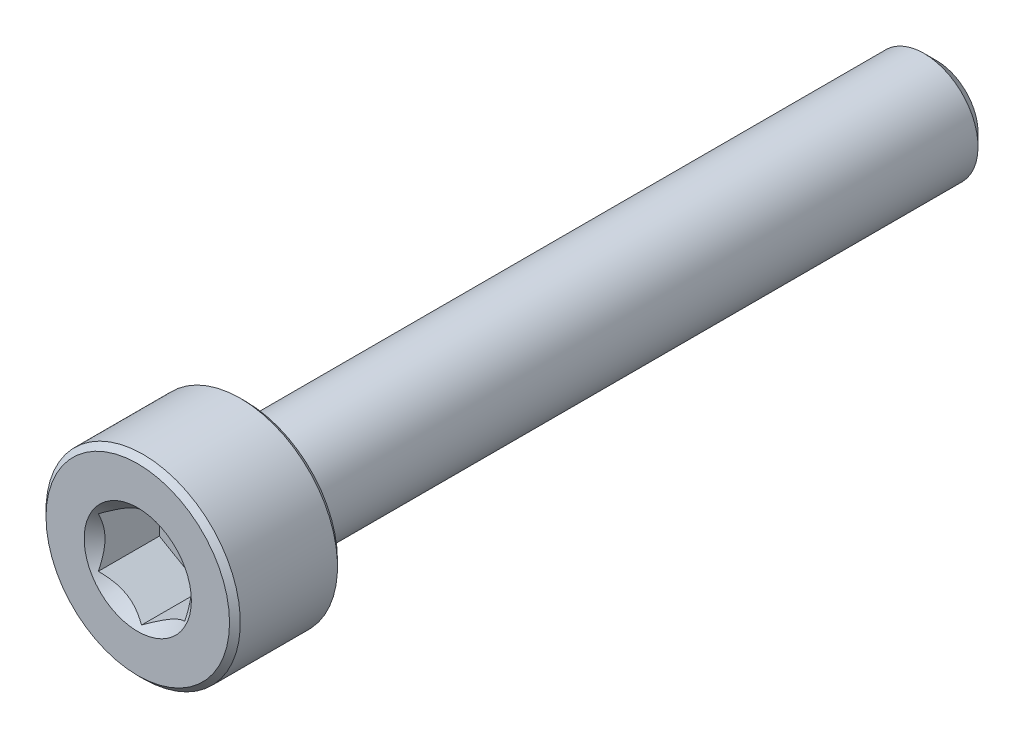
SolidWorks part; units mm, degrees
ref_plane "Front Plane" through (0, 0, 0) normal (0, 0, 1) x (1, 0, 0)
ref_plane "Top Plane" through (0, 0, 0) normal (0, 1, 0) x (1, 0, 0)
ref_plane "Right Plane" through (0, 0, 0) normal (1, 0, 0) x (0, 0, -1)
sketch "Sketch1" plane through (0, 0, 0) normal (1, 0, 0) x (0, 0, -1)
  line L0 (-9.25, 0) -> (9.25, 0) construction
  line L1 (9.25, 0) -> (9.25, 0.9577) construction
  line L2 (9.25, 0.9577) -> (8.9577, 1.25) construction
  line L3 (8.9577, 1.25) -> (8.9125, 1.25) construction
  line L4 (8.9125, 1.25) -> (-6.75, 1.25) construction
  line L5 (-6.75, 1.25) -> (-6.75, 2.25) construction
  line L6 (-6.75, 2.25) -> (-9.25, 2.25) construction
  line L7 (-9.25, 2.25) -> (-9.25, 0) construction
  line L8 (9.25, 0.9577) -> (9.25, 1.25) construction
  line L9 (9.2219, 1.2987) -> (9.4469, 0.909) construction
  line L10 (9.4469, 0.909) -> (9.6719, 1.2987) construction
  line L11 (9.6719, 1.2987) -> (9.2219, 1.2987) construction
  line L12 (9.4469, 1.2987) -> (9.4469, 1.25) construction
  line L13 (9.4469, 0.909) -> (9.4469, 0.9577) construction
  line L14 (9.4187, 0.9577) -> (9.475, 0.9577) construction
  line L15 (9.25, 1.25) -> (9.6437, 1.25) construction
  line L16 (9.2359, 1.2744) -> (9.6578, 1.2744) construction
  line L17 (9.25, 0) -> (9.25, -1.25) construction
  line L18 (-6.875, 2.25) -> (-6.75, 2.125) construction
  line L19 (-9.125, 2.25) -> (-9.25, 2.125) construction
  line L20 (-6.75, 1.25) -> (-6.75, 0) construction
  line L21 (-6.75, 0.625) -> (-1.4167, 0.625) construction
  line L22 (-1.4167, 0.625) -> (3.9167, 0.625) construction
  line L23 (3.9167, 0.625) -> (9.25, 0.625) construction
  line L24 (-1.4167, 0.625) -> (-1.4167, 1.25) construction
  line L25 (-1.4167, 1.25) -> (-1.4167, 2.25) construction
  line L26 (3.9167, 0.625) -> (3.9167, 2.25) construction
  point P0 (-9.25, 1)
  point P3 (8.125, 1.25)
  point P4 (0, 0)
  point P18 (3.9167, 1.25)
  point P22 (9.4469, 0.9577)
  point P24 (8.9125, 1.25)
  point P25 (9.4469, 1.25)
  point P28 (9.4469, 1.2744)
  point P29 (8.125, -1.25)
  point P30 (-1.4167, 1.25)
  point P31 (-8, 2.25)
  point P37 (-7.1875, 2.25)
  point P38 (-9.0625, 2.25)
  point P45 (-1.4167, 0.625)
  point P46 (3.9167, 0.625)
  dimension "D2" = 0.0563
  dimension "D7" = 0.125
  dimension "D8" = 0.125
  dimension "D9" = 0.125
  dimension "D10" = 0.0625
  dimension "D11" = 0.3125
  dimension "Drive Size" = 2
  dimension "Head Diameter" = 4.5
  dimension "Head Height" = 2.5
  dimension "Thread Pitch" = 0.45
  dimension "Thread Dia" = 2.5
  dimension "Length" = 16
  dimension "D12" = 0.3375
  dimension "D4" = 1.125
  dimension "D3" = 45
sketch "Sketch2" plane through (0, 0, 0) normal (1, 0, 0) x (0, 0, -1)
  line L0 (-9.25, 0) -> (-9.25, 2.125)
  line L1 (-9.125, 2.25) -> (-6.875, 2.25)
  line L2 (-6.75, 2.125) -> (-6.75, 1.375)
  line L4 (8.9577, 1.25) -> (9.25, 0.9577)
  line L5 (9.25, 0.9577) -> (9.25, 0)
  line L6 (-6.75, 2.25) -> (-9.25, 2.25) construction
  line L7 (9.25, 0) -> (-9.25, 0)
  line L8 (-9.125, 2.25) -> (-9.25, 2.125) construction
  line L10 (-9.125, 2.25) -> (-9.25, 2.125)
  line L14 (-6.875, 2.25) -> (-6.75, 2.125) construction
  line L16 (-6.875, 2.25) -> (-6.75, 2.125)
  line L17 (-6.75, 1.25) -> (-6.75, 2.25) construction
  line L19 (-6.625, 1.25) -> (8.9577, 1.25)
  line L20 (8.9125, 1.25) -> (-6.75, 1.25) construction
  arc A1 (-6.75, 1.375) -> (-6.625, 1.25) centre (-6.625, 1.375) ccw
  dimension "D3" = 0.125
revolve "Revolve1" add sketch "Sketch2" angle 360 about L7
sketch "Sketch3" plane through (0, 0, 9.25) normal (0, 0, 1) x (1, 0, 0)
  line L1 (1, -0.5774) -> (1, 0.5774)
  line L2 (1, 0.5774) -> (0, 1.1547)
  line L3 (0, 1.1547) -> (-1, 0.5774)
  line L4 (-1, 0.5774) -> (-1, -0.5774)
  line L5 (-1, -0.5774) -> (0, -1.1547)
  line L6 (0, -1.1547) -> (1, -0.5774)
  circle A0 centre (0, 0) radius 1 construction
  circle A1 centre (0, 0) radius 2.25 construction
  circle A2 centre (0, 0) radius 2.25 construction
  circle A3 centre (0, 0) radius 1.1547 construction
  point P13 (0, 0)
  dimension "D1" = 2.3094
extrude "Cut-Extrude1" cut sketch "Sketch3" against normal offset from surface (1.5 mm away) 1 up to face at (0, 2.125, 6.75)
sketch "Sketch4" plane through (0, 0, 9.25) normal (0, 0, 1) x (1, 0, 0)
  circle A0 centre (0, 0) radius 1.2413
  dimension "D1" = 2.4826
extrude "Cut-Extrude2" cut sketch "Sketch4" against normal up to vertex (1.25 mm away) draft 45 up to point (0, 2.25, 8)
sketch "Sketch11" plane through (0, 0, 0) normal (1, 0, 0) x (0, 0, -1)
  line L0 (-9.25, 0) -> (9.25, 0) construction
  line L1 (-9.25, 0) -> (9.25, 0) construction
  line L2 (-3.75, 0) -> (-3.75, 1.25) construction
  line L3 (8.9125, 1.25) -> (-6.75, 1.25) construction
  line L4 (6.25, 0) -> (6.25, 1.25) construction
  line L6 (9.25, 0.9577) -> (9.25, 1.25) construction
  point P2 (-3.75, 0)
  point P3 (6.25, 0)
  dimension "D1" = 3
  dimension "D2" = 3
sketch "Sketch6" plane through (0, 0, -9.25) normal (0, 0, -1) x (-1, 0, 0)
  circle A0 centre (0, 0) radius 1.25
curve "Helix/Spiral1" pitch 0.45 height 16.45 turns 36.5556
sketch "Sketch10" plane through (0, 0, 0) normal (1, 0, 0) x (0, 0, -1)
  line L0 (-6.625, -2.25) -> (-6.625, 2.25)
  line L5 (-9.25, 0) -> (9.25, 0) construction
  line L6 (-6.625, 1.25) -> (-6.625, -1.25) construction
  point P3 (-6.625, 0)
split "Split1" trim tools "Sketch10" bodies to split 106 resulting bodies 114 115
sketch "Sketch8" plane through (0, 0, 0) normal (1, 0, 0) x (0, 0, -1)
  line L0 (-6.75, 0) -> (-6.75, 1.25)
  line L1 (-6.625, -1.25) -> (-6.625, 1.25) construction
  line L2 (-6.75, 1.25) -> (-6.625, 1.25)
  line L4 (-6.625, 1.25) -> (-5.9033, 0)
  line L5 (-5.9033, 0) -> (-6.75, 0)
  line L6 (8.9125, 1.25) -> (-6.75, 1.25) construction
  line L7 (-9.25, 0) -> (9.25, 0) construction
  dimension "D1" = 60
revolve "Revolve2" add sketch "Sketch8" angle 360 about L5
equation "\"D2@Sketch1\" = \"Thread Pitch@Sketch1\" / 8"
equation "\"D4@Helix/Spiral1\" = \"Thread Pitch@Sketch1\""
equation "\"D7@Sketch1\" = \"Head Height@Sketch1\" * .05"
equation "\"D8@Sketch1\"=\"D7@Sketch1\""
equation "\"D9@Sketch1\"=\"D7@Sketch1\""
equation "\"D10@Sketch1\"=\"D7@Sketch1\"/2"
equation "\"D11@Sketch1\"=\"D10@Sketch1\"*5"
equation "\"D4@Sketch1\"=\"Thread Pitch@Sketch1\"*2.5"
equation "\"D12@Sketch1\"=\"Thread Pitch@Sketch1\"*.75"
equation "\"D3@Helix/Spiral1\"=\"Length@Sketch1\"+\"Thread Pitch@Sketch1\""
equation "\"D3@Sketch2\"=\"Thread Dia@Sketch1\"*0.05"
equation "\"D1@Sketch11\"=\"Length@Sketch1\"*0.1875"
equation "\"D2@Sketch11\"=\"D1@Sketch11\""
equation "\"D1@Sketch4\"=\"D1@Sketch3\"*1.075"
